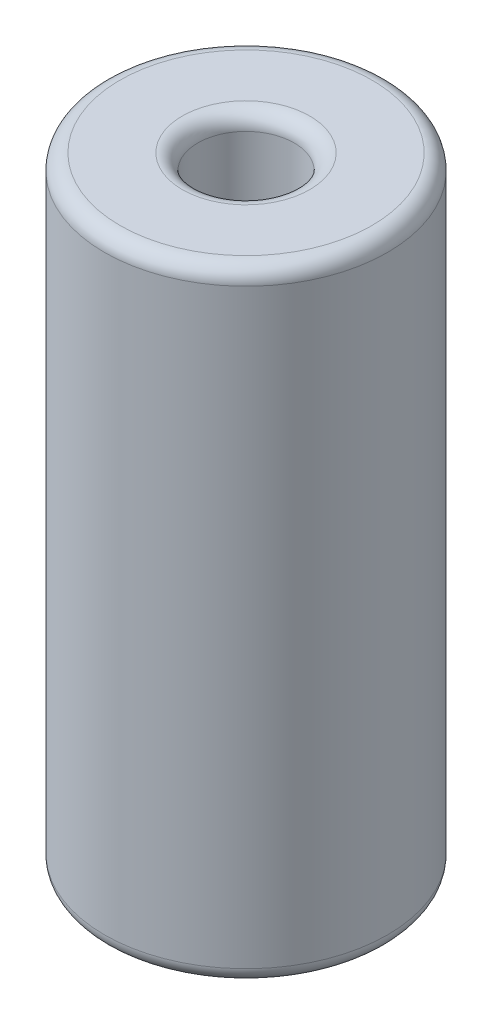
SolidWorks part; units mm, degrees
ref_plane "Front Plane" through (0, 0, 0) normal (0, 0, 1) x (1, 0, 0)
ref_plane "Top Plane" through (0, 0, 0) normal (0, 1, 0) x (1, 0, 0)
ref_plane "Right Plane" through (0, 0, 0) normal (1, 0, 0) x (0, 0, -1)
sketch "Sketch1" plane through (0, 0, 0) normal (0, 1, 0) x (1, 0, 0)
  circle A0 centre (0, 0) radius 1.55
  circle A1 centre (0, 0) radius 4.55
  dimension "D1" = 3.1
  dimension "D2" = 3
extrude "Boss-Extrude1" add sketch "Sketch1" along normal blind 20
fillet "Fillet1" radius 0.5 4 edges at (0, 0, 1.55) (0, 20, 1.55) (0, 0, 4.55) (0, 20, 4.55)
